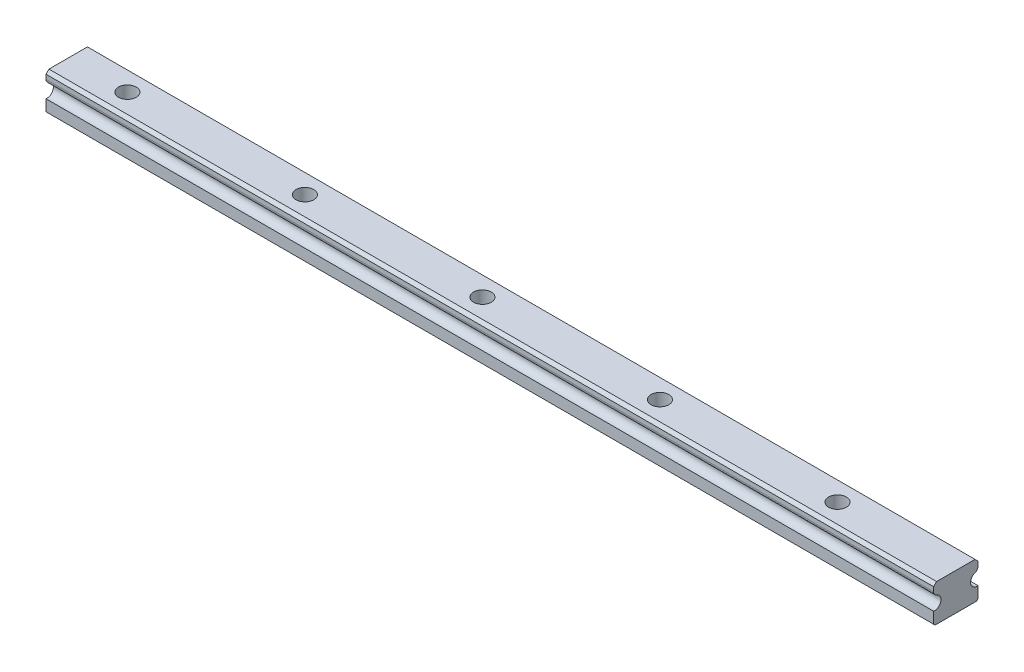
SolidWorks part; units mm, degrees
ref_plane "Front Plane" through (0, 0, 0) normal (0, 0, 1) x (1, 0, 0)
ref_plane "Top Plane" through (0, 0, 0) normal (0, 1, 0) x (1, 0, 0)
ref_plane "Right Plane" through (0, 0, 0) normal (1, 0, 0) x (0, 0, -1)
ref_plane "Plane1" through (-20, 0, 0) normal (1, 0, 0) x (0, 0, -1)
ref_plane "Dim. L" through (280, 0, 0) normal (1, 0, 0) x (0, 0, -1)
ref_plane "Plane2" through (-10, 0, 0) normal (1, 0, 0) x (0, 0, -1)
ref_plane "Plane3" through (270, 0, 0) normal (1, 0, 0) x (0, 0, -1)
ref_plane "Plane4" through (0, 24, 0) normal (0, 1, 0) x (1, 0, 0)
ref_plane "Plane5" through (-20, 0, 0) normal (1, 0, 0) x (0, 0, -1)
ref_plane "Plane6" through (280, 0, 0) normal (1, 0, 0) x (0, 0, -1)
sketch "Sketch1" plane through (-20, 0, 0) normal (1, 0, 0) x (0, 0, -1)
  line L0 (0, 0) -> (0, 12.5) construction
  line L1 (6.5, 12.5) -> (7.5, 11.5)
  line L2 (7.5, 11.5) -> (7.5, 10)
  line L3 (7.5, 4.3206) -> (7.5, 0.5)
  line L4 (7.5, 0.5) -> (7, 0)
  line L20 (-6.5, 12.5) -> (-7.5, 11.5)
  line L21 (-7.5, 11.5) -> (-7.5, 10)
  line L22 (-7.5, 4.3206) -> (-7.5, 0.5)
  line L23 (-7.5, 0.5) -> (-7, 0)
  line L24 (-7, 0) -> (7, 0)
  line L29 (6.5, 12.5) -> (-6.5, 12.5)
  arc A0 (7.5, 10) -> (6.4865, 8.5811) centre (6, 10) cw
  arc A1 (7.5, 4.3206) -> (6.4865, 8.5811) centre (7.2, 6.5) cw
  arc A8 (-7.5, 10) -> (-6.4865, 8.5811) centre (-6, 10) ccw
  arc A9 (-7.5, 4.3206) -> (-6.4865, 8.5811) centre (-7.2, 6.5) ccw
  dimension "MSM_3" = 2.2
  dimension "FIX_3" = 1.5
  dimension "FIX_2" = 45
  dimension "MSM_4" = 1
  dimension "FIX_1" = 45
  dimension "MSM_2" = 10
  dimension "W1" = 15
  dimension "Ca" = 0.5
  dimension "MSM_1" = 6.5
  dimension "H1" = 12.5
extrude "Boss-Extrude1" add sketch "Sketch1" along normal blind 300
hole_wizard "Cap Screw1" positions "Sketch3" profile "Sketch2" counterbore size "M3" standard "JIS" end condition through all
sketch "Sketch3" plane through (0, 12.5, 0) normal (0, 1, 0) x (1, 0, 0)
  point P0 (0, 0)
  point P8 (60, 0)
  point P9 (120, 0)
  point P10 (180, 0)
  point P11 (240, 0)
  point P12 (300, 0)
  point P13 (360, 0)
  point P14 (420, 0)
  dimension "F" = 60
  dimension "M" = 8
sketch "Sketch2" plane through (0, 12.5, 0) normal (1, 0, 0) x (0, 0, 1)
  line L0 (0, 0) -> (0, 12.5)
  line L1 (0, 12.5) -> (1.75, 12.5)
  line L3 (1.75, 12.5) -> (1.75, 4.5)
  line L4 (1.75, 4.5) -> (3, 4.5)
  line L5 (3, 4.5) -> (3, 0)
  line L7 (3, 0) -> (0, 0)
  line L11 (0, 0) -> (0, 12.5) construction
  dimension "D1_s" = 3.5
  dimension "Thru Hole Depth" = 12.5
  dimension "D2_s" = 6
  dimension "H_s" = 4.5
other "SurfaceCut1" [suppressed]
other "SurfaceCut2" [suppressed]
hole_wizard "Tap1" [suppressed] positions "Sketch5" profile "Sketch4" hole size "M3x0.5" standard "JIS"
sketch "Sketch5" [suppressed] plane through (-20, 0, 0) normal (1, 0, 0) x (0, 0, -1)
  point P0 (0, 6)
  dimension "MSM_5" = 6
sketch "Sketch4" [suppressed] plane through (-20, 6, 0) normal (0, 1, 0) x (0, 0, 1)
  line L0 (0, 0) -> (0, 5.7388)
  line L1 (0, 5.7388) -> (1.2295, 5)
  line L2 (1.2295, 5) -> (1.2295, 0)
  line L5 (1.2295, 0) -> (0, 0)
  line L10 (0, 5.7388) -> (-1.2295, 5) construction
  line L11 (0, 0) -> (0, 5.7388) construction
  dimension "STD_3" = 2.459
  dimension "STL_2" = 5
  dimension "Drill Angle" = 118
cosmetic thread "Thread5" [suppressed] parameters "NFIX_1"=3
hole_wizard "Tap2" [suppressed] positions "Sketch7" profile "Sketch6" hole size "M3x0.5" standard "JIS"
sketch "Sketch7" [suppressed] plane through (80, 0, 0) normal (1, 0, 0) x (0, 0, -1)
  point P0 (0, 6)
  dimension "MSM_5" = 6
sketch "Sketch6" [suppressed] plane through (80, 6, 0) normal (0, 1, 0) x (0, 0, -1)
  line L0 (0, 0) -> (0, 5.7388)
  line L1 (0, 5.7388) -> (1.2295, 5)
  line L2 (1.2295, 5) -> (1.2295, 0)
  line L5 (1.2295, 0) -> (0, 0)
  line L10 (0, 5.7388) -> (-1.2295, 5) construction
  line L11 (0, 0) -> (0, 5.7388) construction
  dimension "STD_3" = 2.459
  dimension "STL_2" = 5
  dimension "Drill Angle" = 118
cosmetic thread "Thread6" [suppressed] parameters "NFIX_2"=3
hole_wizard "Tap3" [suppressed] positions "Sketch9" profile "Sketch8" hole size "M3x0.5" standard "JIS"
sketch "Sketch9" [suppressed] plane through (-20, 0, 0) normal (1, 0, 0) x (0, 0, -1)
  point P0 (0, 13)
  dimension "KSS_1" = 13
sketch "Sketch8" [suppressed] plane through (-20, 13, 0) normal (0, 1, 0) x (0, 0, 1)
  line L0 (0, 0) -> (0, 5.7388)
  line L1 (0, 5.7388) -> (1.2295, 5)
  line L2 (1.2295, 5) -> (1.2295, 0)
  line L5 (1.2295, 0) -> (0, 0)
  line L10 (0, 5.7388) -> (-1.2295, 5) construction
  line L11 (0, 0) -> (0, 5.7388) construction
  dimension "STD_3" = 2.459
  dimension "STL_2" = 5
  dimension "Drill Angle" = 118
cosmetic thread "Thread7" [suppressed] parameters "NFIX_3"=3
hole_wizard "Tap4" [suppressed] positions "Sketch11" profile "Sketch10" hole size "M3x0.5" standard "JIS"
sketch "Sketch11" [suppressed] plane through (80, 0, 0) normal (1, 0, 0) x (0, 0, -1)
  point P0 (0, 13)
  dimension "KSS_2" = 13
sketch "Sketch10" [suppressed] plane through (80, 13, 0) normal (0, 1, 0) x (0, 0, -1)
  line L0 (0, 0) -> (0, 5.7388)
  line L1 (0, 5.7388) -> (1.2295, 5)
  line L2 (1.2295, 5) -> (1.2295, 0)
  line L5 (1.2295, 0) -> (0, 0)
  line L10 (0, 5.7388) -> (-1.2295, 5) construction
  line L11 (0, 0) -> (0, 5.7388) construction
  dimension "STD_3" = 2.459
  dimension "STL_2" = 5
  dimension "Drill Angle" = 118
cosmetic thread "Thread8" [suppressed] parameters "NFIX_4"=3
hole_wizard "Tap5" [suppressed] positions "Sketch14" profile "Sketch13" hole size "M3x0.5" standard "JIS"
sketch "Sketch14" [suppressed] plane through (-20, 0, 0) normal (1, 0, 0) x (0, 0, -1)
  point P0 (0, 6)
  dimension "MSM_5" = 6
sketch "Sketch13" [suppressed] plane through (-20, 6, 0) normal (0, 1, 0) x (0, 0, 1)
  line L0 (0, 0) -> (0, 5.7388)
  line L1 (0, 5.7388) -> (1.2295, 5)
  line L2 (1.2295, 5) -> (1.2295, 0)
  line L5 (1.2295, 0) -> (0, 0)
  line L10 (0, 5.7388) -> (-1.2295, 5) construction
  line L11 (0, 0) -> (0, 5.7388) construction
  dimension "STD_3" = 2.459
  dimension "STL_2" = 5
  dimension "Drill Angle" = 118
cosmetic thread "Thread9" [suppressed] parameters "NFIX_5"=3
hole_wizard "Tap6" [suppressed] positions "Sketch16" profile "Sketch15" hole size "M3x0.5" standard "JIS"
sketch "Sketch16" [suppressed] plane through (80, 0, 0) normal (1, 0, 0) x (0, 0, -1)
  point P0 (0, 6)
  dimension "MSM_5" = 6
sketch "Sketch15" [suppressed] plane through (80, 6, 0) normal (0, 1, 0) x (0, 0, -1)
  line L0 (0, 0) -> (0, 5.7388)
  line L1 (0, 5.7388) -> (1.2295, 5)
  line L2 (1.2295, 5) -> (1.2295, 0)
  line L5 (1.2295, 0) -> (0, 0)
  line L10 (0, 5.7388) -> (-1.2295, 5) construction
  line L11 (0, 0) -> (0, 5.7388) construction
  dimension "STD_3" = 2.459
  dimension "STL_2" = 5
  dimension "Drill Angle" = 118
cosmetic thread "Thread10" [suppressed] parameters "NFIX_6"=3
hole_wizard "Tap7" [suppressed] positions "Sketch18" profile "Sketch17" hole size "M3x0.5" standard "JIS"
sketch "Sketch18" [suppressed] plane through (-20, 0, 0) normal (1, 0, 0) x (0, 0, -1)
  point P0 (0, 13)
  dimension "KSS_3" = 13
sketch "Sketch17" [suppressed] plane through (-20, 13, 0) normal (0, 1, 0) x (0, 0, 1)
  line L0 (0, 0) -> (0, 5.7388)
  line L1 (0, 5.7388) -> (1.2295, 5)
  line L2 (1.2295, 5) -> (1.2295, 0)
  line L5 (1.2295, 0) -> (0, 0)
  line L10 (0, 5.7388) -> (-1.2295, 5) construction
  line L11 (0, 0) -> (0, 5.7388) construction
  dimension "STD_3" = 2.459
  dimension "STL_2" = 5
  dimension "Drill Angle" = 118
cosmetic thread "Thread11" [suppressed] parameters "NFIX_7"=3
hole_wizard "Tap8" [suppressed] positions "Sketch20" profile "Sketch19" hole size "M3x0.5" standard "JIS"
sketch "Sketch20" [suppressed] plane through (80, 0, 0) normal (1, 0, 0) x (0, 0, -1)
  point P0 (0, 13)
  dimension "KSS_4" = 13
sketch "Sketch19" [suppressed] plane through (80, 13, 0) normal (0, 1, 0) x (0, 0, -1)
  line L0 (0, 0) -> (0, 5.7388)
  line L1 (0, 5.7388) -> (1.2295, 5)
  line L2 (1.2295, 5) -> (1.2295, 0)
  line L5 (1.2295, 0) -> (0, 0)
  line L10 (0, 5.7388) -> (-1.2295, 5) construction
  line L11 (0, 0) -> (0, 5.7388) construction
  dimension "STD_3" = 2.459
  dimension "STL_2" = 5
  dimension "Drill Angle" = 118
cosmetic thread "Thread12" [suppressed] parameters "NFIX_8"=3
scale "缩放比例2" scale about origin uniform scaling yes scale factor 1.7
equation "\"KSS_1@Sketch9\" = \"MSM_5@Sketch5\" + 7"
equation "\"KSS_2@Sketch11\"= \"MSM_5@Sketch5\" + 7"
equation "\"KSS_3@Sketch18\" = \"MSM_5@Sketch5\" + 7"
equation "\"KSS_4@Sketch20\" = \"MSM_5@Sketch5\" + 7"
